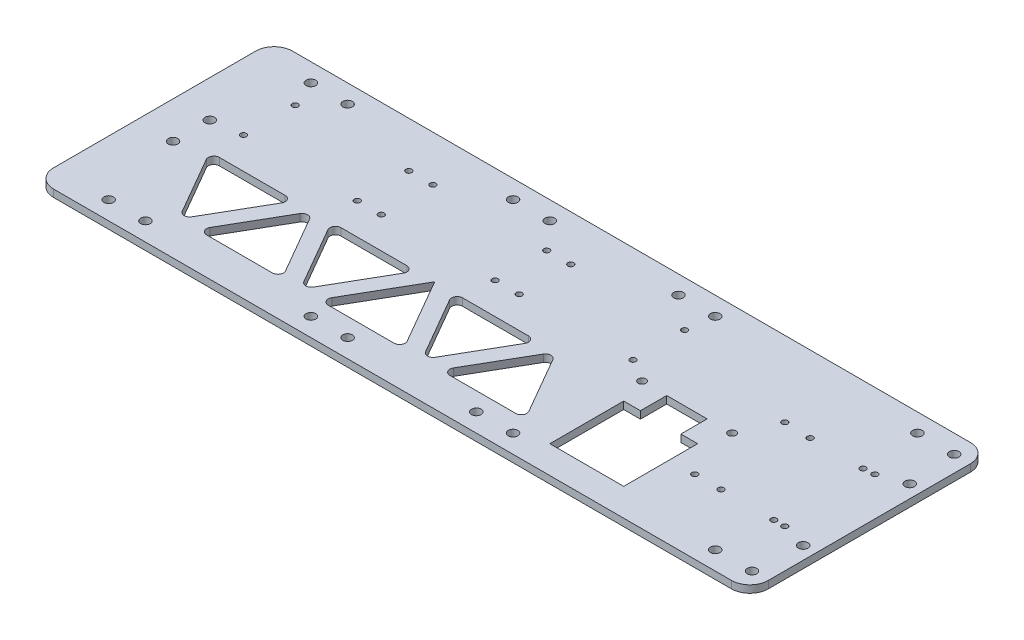
SolidWorks part; units mm, degrees
ref_plane "前视基准面" through (0, 0, 0) normal (0, 0, 1) x (1, 0, 0)
ref_plane "上视基准面" through (0, 0, 0) normal (0, 1, 0) x (1, 0, 0)
ref_plane "右视基准面" through (0, 0, 0) normal (1, 0, 0) x (0, 0, -1)
other "Configuration Table"
sketch "草图1" plane through (0, 0, 0) normal (0, 1, 0) x (1, 0, 0)
  line L1 (0, 0) -> (388.85, 0)
  line L2 (0, 0) -> (0, -130)
  line L3 (0, -130) -> (388.85, -130)
  line L4 (388.85, 0) -> (388.85, -130)
  dimension "D1" = 130
  dimension "D2" = 388.85
extrude "凸台-拉伸1" add sketch "草图1" along normal blind 4
sketch "草图2" plane through (0, 4, 0) normal (0, 1, 0) x (1, 0, 0)
  line L0 (45, -59.5) -> (64, -59.5) construction
  line L1 (41, -59.5) -> (45, -59.5)
  line L2 (41, -59.5) -> (41, -75.5)
  line L3 (41, -75.5) -> (45, -75.5)
  line L4 (45, -59.5) -> (45, -75.5)
  line L5 (64, -59.5) -> (68, -59.5)
  line L6 (64, -59.5) -> (64, -75.5)
  line L7 (64, -75.5) -> (68, -75.5)
  line L8 (68, -59.5) -> (68, -75.5)
  line L9 (36.21, -24.8) -> (98.11, -24.8) construction
  line L10 (36.21, -24.8) -> (36.21, -52.9) construction
  line L11 (36.21, -52.9) -> (98.11, -52.9) construction
  line L12 (98.11, -24.8) -> (98.11, -52.9) construction
  line L13 (54.5, -59.5) -> (54.5, -65.549) construction
  line L14 (0, -65) -> (40, -65) construction
  line L15 (0, 0) -> (0, -130) construction
  line L16 (116, -59.5) -> (120, -59.5)
  line L17 (116, -59.5) -> (116, -75.5)
  line L18 (116, -75.5) -> (120, -75.5)
  line L19 (120, -59.5) -> (120, -75.5)
  line L20 (139, -59.5) -> (143, -59.5)
  line L21 (139, -59.5) -> (139, -75.5)
  line L22 (139, -75.5) -> (143, -75.5)
  line L23 (143, -59.5) -> (143, -75.5)
  line L24 (120, -59.5) -> (139, -59.5) construction
  line L25 (111.21, -24.8) -> (173.11, -24.8) construction
  line L26 (111.21, -24.8) -> (111.21, -52.9) construction
  line L27 (111.21, -52.9) -> (173.11, -52.9) construction
  line L28 (173.11, -24.8) -> (173.11, -52.9) construction
  line L29 (129.5, -59.5) -> (129.5, -65.549) construction
  line L30 (191, -59.5) -> (195, -59.5)
  line L31 (191, -59.5) -> (191, -75.5)
  line L32 (191, -75.5) -> (195, -75.5)
  line L33 (195, -59.5) -> (195, -75.5)
  line L34 (214, -59.5) -> (218, -59.5)
  line L35 (214, -59.5) -> (214, -75.5)
  line L36 (214, -75.5) -> (218, -75.5)
  line L37 (218, -59.5) -> (218, -75.5)
  line L38 (195, -59.5) -> (214, -59.5) construction
  line L39 (186.21, -24.8) -> (248.11, -24.8) construction
  line L40 (186.21, -24.8) -> (186.21, -52.9) construction
  line L41 (186.21, -52.9) -> (248.11, -52.9) construction
  line L42 (248.11, -24.8) -> (248.11, -52.9) construction
  line L43 (204.5, -59.5) -> (204.5, -65.549) construction
  circle A0 centre (36.21, -52.9) radius 1.6
  circle A1 centre (36.21, -24.8) radius 1.6
  circle A2 centre (98.11, -52.9) radius 1.6
  circle A3 centre (98.11, -24.8) radius 1.6
  circle A4 centre (40, -65) radius 1 construction
  circle A5 centre (111.21, -52.9) radius 1.6
  circle A6 centre (111.21, -24.8) radius 1.6
  circle A7 centre (173.11, -52.9) radius 1.6
  circle A8 centre (173.11, -24.8) radius 1.6
  circle A9 centre (115, -65) radius 1 construction
  circle A10 centre (186.21, -52.9) radius 1.6
  circle A11 centre (186.21, -24.8) radius 1.6
  circle A12 centre (248.11, -52.9) radius 1.6
  circle A13 centre (248.11, -24.8) radius 1.6
  circle A14 centre (190, -65) radius 1 construction
  dimension "D9" = 2
  dimension "D13" = 3.2
  dimension "D1" = 4
  dimension "D2" = 4
  dimension "D3" = 19
  dimension "D4" = 16
  dimension "D5" = 28.1
  dimension "D6" = 61.9
  dimension "D7" = 12.1
  dimension "D8" = 3.79
  dimension "D10" = 14.5
  dimension "D11" = 5.5
  dimension "D12" = 40
  dimension "D14" = 3
extrude "切除-拉伸1" cut sketch "草图2" against normal blind 4 contours A0 | A2 | A3 | A6 | A5 | A8 | A7 | A11 | A10 | A12 | A1 | A13
sketch "草图3" plane through (0, 4, 0) normal (0, 1, 0) x (1, 0, 0)
  line L0 (0, -65) -> (25.2073, -65) construction
  line L1 (0, 0) -> (0, -130) construction
  line L2 (20, -75) -> (20, -55) construction
  circle A0 centre (20, -75) radius 2.6
  circle A1 centre (20, -55) radius 2.6
  dimension "D1" = 5.2
  dimension "D2" = 20
  dimension "D3" = 20
extrude "切除-拉伸2" cut sketch "草图3" against normal through all
sketch "草图4" plane through (0, 4, 0) normal (0, 1, 0) x (1, 0, 0)
  line L0 (67.16, -24.8) -> (67.16, 18.7842) construction
  line L1 (0, -130) -> (300, -130)
  line L2 (0, -130) -> (0, -180)
  line L3 (0, -180) -> (300, -180)
  line L4 (300, -130) -> (300, -180)
  line L5 (36.21, -24.8) -> (98.11, -24.8) construction
  line L6 (142.16, -24.8) -> (142.16, 18.7842) construction
  line L7 (111.21, -24.8) -> (173.11, -24.8) construction
  line L8 (217.16, -24.8) -> (217.16, 18.7842) construction
  line L9 (186.21, -24.8) -> (248.11, -24.8) construction
  line L10 (42.16, 30) -> (42.16, 0)
  line L11 (42.16, 30) -> (92.16, 30)
  line L12 (42.16, 0) -> (92.16, 0)
  line L13 (92.16, 30) -> (92.16, 0)
  line L14 (42.16, 30) -> (92.16, 0) construction
  line L15 (42.16, 0) -> (92.16, 30) construction
  line L16 (117.16, 30) -> (117.16, 0)
  line L17 (117.16, 30) -> (167.16, 30)
  line L18 (167.16, 30) -> (167.16, 0)
  line L19 (117.16, 0) -> (167.16, 0)
  line L20 (192.16, 30) -> (192.16, 0)
  line L21 (192.16, 30) -> (242.16, 30)
  line L22 (242.16, 30) -> (242.16, 0)
  line L23 (192.16, 0) -> (242.16, 0)
  point P18 (67.16, 15)
  dimension "D1" = 300
  dimension "D2" = 50
  dimension "D3" = 50
  dimension "D4" = 30
  dimension "D5" = 3
extrude "凸台-拉伸2" [suppressed] add sketch "草图4" against normal up to surface (4 mm away)
sketch "草图5" plane through (0, 4, 0) normal (0, 1, 0) x (1, 0, 0)
  line L1 (30, -10) -> (50, -10) construction
  line L2 (0, 0) -> (0, -130) construction
  line L3 (0, -65) -> (40, -65) construction
  line L4 (0, -65) -> (40, -65) construction
  line L5 (140, -10) -> (160, -10) construction
  line L6 (380, -120) -> (360, -120) construction
  line L7 (230, -10) -> (250, -10) construction
  line L8 (230, -120) -> (250, -120) construction
  line L9 (380, -10) -> (360, -10) construction
  line L10 (140, -120) -> (160, -120) construction
  line L11 (30, -120) -> (50, -120) construction
  circle A0 centre (30, -10) radius 2.6
  circle A1 centre (50, -10) radius 2.6
  circle A4 centre (140, -10) radius 2.6
  circle A5 centre (160, -10) radius 2.6
  circle A8 centre (230, -10) radius 2.6
  circle A9 centre (250, -10) radius 2.6
  circle A12 centre (360, -10) radius 2.6
  circle A13 centre (380, -10) radius 2.6
  circle A16 centre (380, -120) radius 2.6
  circle A17 centre (360, -120) radius 2.6
  circle A18 centre (250, -120) radius 2.6
  circle A19 centre (230, -120) radius 2.6
  circle A20 centre (160, -120) radius 2.6
  circle A21 centre (140, -120) radius 2.6
  circle A22 centre (50, -120) radius 2.6
  circle A23 centre (30, -120) radius 2.6
  dimension "D1" = 5.2
  dimension "D11" = 110
  dimension "D12" = 90
  dimension "D13" = 130
  dimension "D2" = 55
  dimension "D3" = 20
  dimension "D4" = 30
  dimension "D5" = 20
  dimension "D7" = 20
  dimension "D9" = 20
extrude "切除-拉伸3" cut sketch "草图5" against normal through all
sketch "草图6" plane through (0, 4, 0) normal (0, 1, 0) x (1, 0, 0)
  line L8 (378.85, -112) -> (334.85, -112)
  line L9 (334.85, -112) -> (334.85, -101)
  line L12 (334.85, -101) -> (320.85, -101)
  line L13 (320.85, -101) -> (320.85, -79)
  line L16 (320.85, -79) -> (334.85, -79)
  line L17 (334.85, -79) -> (334.85, -68)
  line L18 (334.85, -68) -> (378.85, -68)
  line L19 (378.85, -68) -> (378.85, -112)
  line L20 (0, -130) -> (388.85, -130) construction
  line L21 (388.85, -130) -> (388.85, 0) construction
  circle A6 centre (324.35, -114.5) radius 2.1
  circle A7 centre (324.35, -65.5) radius 2.1
  dimension "D3" = 22
  dimension "D11" = 4.2
  dimension "D1" = 44
  dimension "D2" = 44
  dimension "D4" = 11
  dimension "D5" = 14
  dimension "D6" = 14
  dimension "D7" = 13.5
  dimension "D8" = 13.5
  dimension "D9" = 54.5
  dimension "D10" = 54.5
  dimension "D12" = 18
  dimension "D13" = 10
extrude "切除-拉伸4" [suppressed] cut sketch "草图6" against normal through all
sketch "草图7" plane through (0, 4, 0) normal (0, 1, 0) x (1, 0, 0)
  line L0 (305.2, -74.8) -> (305.2, -115)
  line L1 (265, -74.8) -> (274.1, -74.8)
  line L2 (265, -74.8) -> (265, -115)
  line L3 (265, -115) -> (305.2, -115)
  line L4 (296.1, -60.5) -> (274.1, -60.5)
  line L5 (274.1, -60.5) -> (274.1, -74.8)
  line L6 (296.1, -74.8) -> (305.2, -74.8)
  line L7 (296.1, -60.5) -> (296.1, -74.8)
  line L8 (260.6, -60.4) -> (309.6, -60.4) construction
  line L12 (285.1, -115) -> (285.1, -60.5) construction
  line L13 (0, -130) -> (388.85, -130) construction
  line L14 (0, 0) -> (0, -130) construction
  circle A0 centre (260.6, -60.4) radius 2.1
  circle A1 centre (309.6, -60.4) radius 2.1
  point P10 (285.1, -60.5)
  dimension "D3" = 4.2
  dimension "D11" = 265
  dimension "D1" = 40.2
  dimension "D2" = 14.3
  dimension "D4" = 22
  dimension "D5" = 9.1
  dimension "D6" = 40.2
  dimension "D7" = 13.5
  dimension "D8" = 13.5
  dimension "D9" = 9.1
  dimension "D10" = 40.2
  dimension "D12" = 15
  dimension "D13" = 54.6
extrude "切除-拉伸5" cut sketch "草图7" against normal through all
sketch "草图8" plane through (0, 4, 0) normal (0, 1, 0) x (1, 0, 0)
  line L0 (0, -130) -> (388.85, -130) construction
  line L1 (318.85, -90) -> (367.85, -90) construction
  line L2 (318.85, -90) -> (318.85, -41) construction
  line L3 (318.85, -41) -> (367.85, -41) construction
  line L4 (367.85, -90) -> (367.85, -41) construction
  line L5 (388.85, -130) -> (388.85, 0) construction
  circle A0 centre (318.85, -41) radius 1.6
  circle A1 centre (367.85, -41) radius 1.6
  circle A2 centre (318.85, -90) radius 1.6
  circle A3 centre (367.85, -90) radius 1.6
  dimension "D3" = 3.2
  dimension "D1" = 49
  dimension "D2" = 49
  dimension "D4" = 40
  dimension "D5" = 21
extrude "切除-拉伸6" cut sketch "草图8" against normal through all
sketch "草图9" plane through (0, 4, 0) normal (0, 1, 0) x (1, 0, 0)
  line L0 (0, -130) -> (388.85, -130) construction
  line L1 (333.15, -41.5) -> (361.85, -41.5) construction
  line L2 (333.15, -41.5) -> (333.15, -90) construction
  line L3 (333.15, -90) -> (361.85, -90) construction
  line L4 (361.85, -41.5) -> (361.85, -90) construction
  line L5 (388.85, -130) -> (388.85, 0) construction
  circle A0 centre (333.15, -41.5) radius 1.6
  circle A1 centre (361.85, -41.5) radius 1.6
  circle A2 centre (333.15, -90) radius 1.6
  circle A3 centre (361.85, -90) radius 1.6
  dimension "D3" = 3.2
  dimension "D1" = 48.5
  dimension "D2" = 28.7
  dimension "D4" = 40
  dimension "D5" = 27
extrude "切除-拉伸7" cut sketch "草图9" against normal through all
sketch "草图10" plane through (0, 4, 0) normal (0, 1, 0) x (1, 0, 0)
  line L0 (388.85, -65) -> (357.1878, -65) construction
  line L1 (388.85, -130) -> (388.85, 0) construction
  circle A0 centre (381.85, -36) radius 2.6
  circle A1 centre (381.85, -94) radius 2.6
  dimension "D1" = 5.2
  dimension "D3" = 7
  dimension "D2" = 58
extrude "切除-拉伸8" cut sketch "草图10" against normal through all
fillet "圆角1" radius 10 4 edges at (388.85, 2, 0) (388.85, 2, 130) (0, 2, 130) (0, 2, 0)
sketch "草图11" plane through (0, 4, 0) normal (0, 1, 0) x (1, 0, 0)
  line L0 (0, -10) -> (0, -120) construction
  line L1 (58.095, -110.0017) -> (81.19, -70)
  line L2 (81.19, -70) -> (35, -70)
  line L3 (35, -70) -> (58.095, -110.0017)
  line L4 (68.095, -110.0017) -> (114.285, -110.0017)
  line L5 (114.285, -110.0017) -> (91.19, -70)
  line L6 (91.19, -70) -> (68.095, -110.0017)
  line L7 (10, -130) -> (378.85, -130) construction
  line L8 (124.285, -110.0017) -> (147.38, -70)
  line L9 (147.38, -70) -> (101.19, -70)
  line L10 (101.19, -70) -> (124.285, -110.0017)
  line L11 (134.285, -110.0017) -> (180.475, -110.0017)
  line L12 (180.475, -110.0017) -> (157.38, -70)
  line L13 (157.38, -70) -> (134.285, -110.0017)
  line L14 (190.475, -110.0017) -> (213.57, -70)
  line L15 (213.57, -70) -> (167.38, -70)
  line L16 (167.38, -70) -> (190.475, -110.0017)
  line L17 (200.475, -110.0017) -> (246.665, -110.0017)
  line L18 (246.665, -110.0017) -> (223.57, -70)
  line L19 (223.57, -70) -> (200.475, -110.0017)
  circle A0 centre (58.095, -83.3339) radius 13.3339 construction
  circle A1 centre (91.19, -96.6678) radius 13.3339 construction
  dimension "D1" = 35
  dimension "D2" = 60
  dimension "D3" = 46.19
  dimension "D4" = 10
  dimension "D5" = 3
extrude "切除-拉伸9" cut sketch "草图11" against normal through all
fillet "圆角2" radius 3 17 edges at (223.57, 2, 70) (246.665, 2, 110.0017) (200.475, 2, 110.0017) (190.475, 2, 110.0017) (180.475, 2, 110.0017) (134.285, 2, 110.0017) (124.285, 2, 110.0017) (114.285, 2, 110.0017) (68.095, 2, 110.0017) (91.19, 2, 70) (167.38, 2, 70) (101.19, 2, 70) (213.57, 2, 70) (147.38, 2, 70) (81.19, 2, 70) (58.095, 2, 110.0017) (35, 2, 70)
